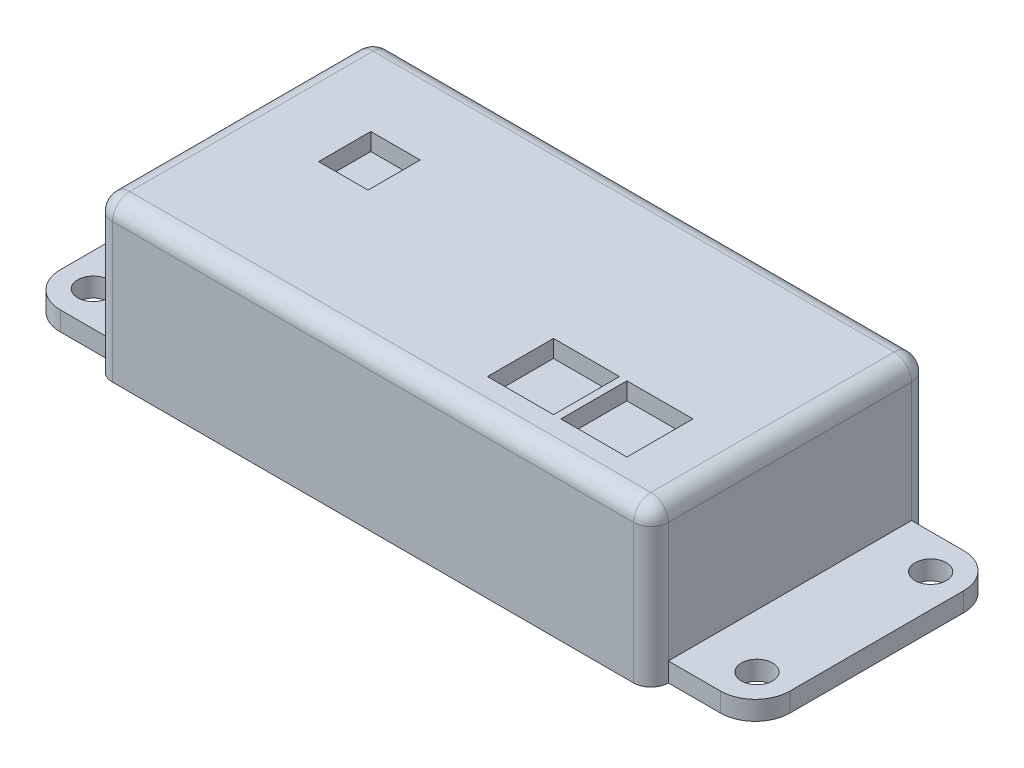
SolidWorks part; units mm, degrees
ref_plane "Front Plane" through (0, 0, 0) normal (0, 0, 1) x (1, 0, 0)
ref_plane "Top Plane" through (0, 0, 0) normal (0, 1, 0) x (1, 0, 0)
ref_plane "Right Plane" through (0, 0, 0) normal (1, 0, 0) x (0, 0, -1)
sketch "Sketch1" plane through (0, 0, 0) normal (0, 1, 0) x (1, 0, 0)
  line L1 (-40.64, 20.32) -> (40.64, 20.32)
  line L2 (-40.64, 20.32) -> (-40.64, -20.32)
  line L3 (-40.64, -20.32) -> (40.64, -20.32)
  line L4 (40.64, 20.32) -> (40.64, -20.32)
  line L5 (-40.64, 20.32) -> (40.64, -20.32) construction
  line L6 (-40.64, -20.32) -> (40.64, 20.32) construction
  point P0 (0, 0)
  dimension "D1" = 81.28
  dimension "D2" = 40.64
extrude "Boss-Extrude1" add sketch "Sketch1" along normal blind 22.86
fillet "Fillet1" radius 2.54 8 edges at (-40.64, 11.43, -20.32) (40.64, 11.43, -20.32) (0, 22.86, -20.32) (-40.64, 22.86, 0) (-40.64, 11.43, 20.32) (40.64, 11.43, 20.32) (40.64, 22.86, 0) (0, 22.86, 20.32)
sketch "Sketch2" plane through (0, 0, 0) normal (0, -1, 0) x (1, 0, 0)
  line L0 (40.64, 17.78) -> (53.34, 17.78)
  line L1 (40.64, 17.78) -> (40.64, -17.78) construction
  line L2 (53.34, 17.78) -> (53.34, -17.78)
  line L3 (53.34, -17.78) -> (40.64, -17.78)
  line L4 (40.64, -17.78) -> (40.64, 17.78)
  point P4 (40.64, 0)
  dimension "D1" = 35.56
  dimension "D2" = 12.7
extrude "Boss-Extrude2" add sketch "Sketch2" against normal blind 2.794
fillet "Fillet2" radius 5.08 2 edges at (53.34, 1.397, -17.78) (53.34, 1.397, 17.78)
sketch "Sketch3" plane through (0, 2.794, 0) normal (0, 1, 0) x (1, 0, 0)
  line L0 (48.514, 12.7) -> (48.514, -12.7) construction
  line L1 (53.34, 12.7) -> (53.34, -12.7) construction
  circle A0 centre (48.514, 12.7) radius 2.286
  circle A1 centre (48.514, -12.7) radius 2.286
  point P4 (48.514, 0)
  dimension "D1" = 4.572
  dimension "D2" = 4.826
  dimension "D3" = 25.4
extrude "Cut-Extrude1" cut sketch "Sketch3" against normal through all
mirror "Mirror1" about plane through (0, 0, 0) normal (1, 0, 0) of "Cut-Extrude1", "Fillet2", "Boss-Extrude2"
sketch "Sketch4" plane through (0, 22.86, 0) normal (0, 1, 0) x (1, 0, 0)
  line L1 (-28.0884, 7.44) -> (-20.8582, 7.44)
  line L2 (-28.0884, 7.44) -> (-28.0884, -0.1919)
  line L3 (-28.0884, -0.1919) -> (-20.8582, -0.1919)
  line L4 (-20.8582, 7.44) -> (-20.8582, -0.1919)
  line L5 (-28.0884, 7.44) -> (-20.8582, -0.1919) construction
  line L6 (-28.0884, -0.1919) -> (-20.8582, 7.44) construction
  line L7 (11.4773, -5.407) -> (21.1293, -5.407)
  line L8 (11.4773, -5.407) -> (11.4773, -15.059)
  line L9 (11.4773, -15.059) -> (21.1293, -15.059)
  line L10 (21.1293, -5.407) -> (21.1293, -15.059)
  line L11 (11.4773, -5.407) -> (21.1293, -15.059) construction
  line L12 (11.4773, -15.059) -> (21.1293, -5.407) construction
  line L13 (22.2069, -5.407) -> (31.8589, -5.407)
  line L14 (22.2069, -5.407) -> (22.2069, -15.059)
  line L15 (22.2069, -15.059) -> (31.8589, -15.059)
  line L16 (31.8589, -5.407) -> (31.8589, -15.059)
  line L17 (22.2069, -5.407) -> (31.8589, -15.059) construction
  line L18 (22.2069, -15.059) -> (31.8589, -5.407) construction
  point P0 (-24.4733, 3.624)
  point P5 (16.3033, -10.233)
  point P10 (27.0329, -10.233)
  dimension "D1" = 1.0775
  dimension "D2" = 9.652
extrude "Cut-Extrude2" cut sketch "Sketch4" against normal blind 2.54
